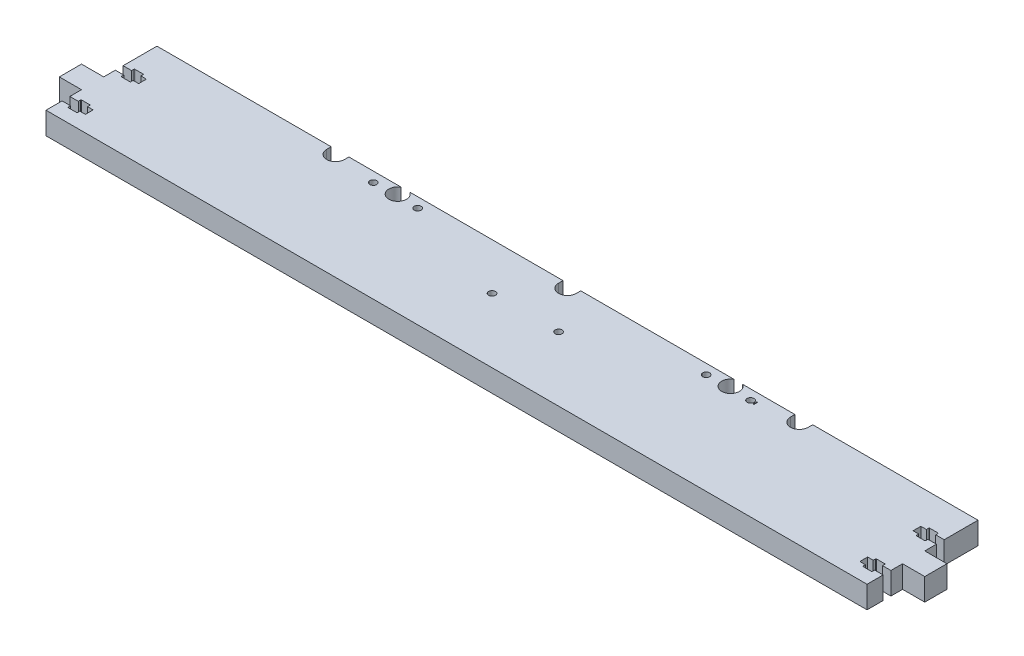
SolidWorks part; units mm, degrees
ref_plane "Front Plane" through (0, 0, 0) normal (0, 0, 1) x (1, 0, 0)
ref_plane "Top Plane" through (0, 0, 0) normal (0, 1, 0) x (1, 0, 0)
ref_plane "Right Plane" through (0, 0, 0) normal (1, 0, 0) x (0, 0, -1)
sketch "Sketch1" plane through (0, 0, 0) normal (0, 1, 0) x (1, 0, 0)
  line L0 (0, 25) -> (0, -25)
  line L1 (-185, 25) -> (0, 25)
  line L2 (-185, 25) -> (-185, -25) construction
  line L3 (-185, -25) -> (0, -25)
  line L4 (-185, -4) -> (-195, -4) construction
  line L5 (-185, 25) -> (0, 0) construction
  line L6 (-185, -25) -> (0, 0) construction
  line L7 (-185, -9) -> (-195, -9)
  line L8 (-195, -9) -> (-195, 1)
  line L9 (-195, 1) -> (-185, 1)
  line L10 (-185, 1) -> (-185, 25)
  line L11 (-185, -9) -> (-185, -25)
  line L47 (0, -25) -> (0, 25) construction
  line L89 (0, -25) -> (0, 25) construction
  point P0 (0, 0)
  dimension "D1" = 185
  dimension "D25" = 25
  dimension "D4" = 50
  dimension "D3" = 21
  dimension "D5" = 10
  dimension "D6" = 10
  dimension "D7" = 5
extrude "MainBody" add sketch "Sketch1" along normal blind 10
sketch "Sketch5" plane through (0, 10, 0) normal (0, 1, 0) x (1, 0, 0)
  line L0 (-185, 8) -> (-174.5, 8) construction
  line L1 (-185, 1) -> (-185, 25) construction
  line L2 (-185, 9.75) -> (-174.5, 9.75) construction
  line L3 (-174.5, 9.75) -> (-174.5, 6.25) construction
  line L4 (-174.5, 6.25) -> (-185, 6.25) construction
  line L5 (-185, 9.75) -> (-181.2, 9.75)
  line L6 (-181.2, 9.75) -> (-181.2, 10.75)
  line L7 (-180.95, 11) -> (-177.25, 11)
  line L8 (-177, 10.75) -> (-177, 9.75)
  line L9 (-177, 9.75) -> (-174.5, 9.75)
  line L10 (-174.5, 9.75) -> (-174.5, 6.25)
  line L11 (-185, 6.25) -> (-185, 9.75)
  line L12 (-195, -9) -> (-195, 1) construction
  line L13 (-185, 6.25) -> (-174.5, 6.25) construction
  line L14 (-177, 6.25) -> (-174.5, 6.25)
  line L15 (-177, 5.25) -> (-177, 6.25)
  line L16 (-180.95, 5) -> (-177.25, 5)
  line L17 (-181.2, 6.25) -> (-181.2, 5.25)
  line L18 (-185, 6.25) -> (-181.2, 6.25)
  line L19 (-185, 1) -> (-185, -9) construction
  line L20 (-195, -4) -> (-185, -4) construction
  line L21 (-195, -9) -> (-195, 1) construction
  line L22 (-185, -14.25) -> (-174.5, -14.25) construction
  line L23 (-174.5, -14.25) -> (-185, -14.25) construction
  line L24 (-174.5, -17.75) -> (-174.5, -14.25) construction
  line L25 (-185, -17.75) -> (-174.5, -17.75) construction
  line L26 (-185, -16) -> (-174.5, -16) construction
  line L27 (-185, -14.25) -> (-181.2, -14.25)
  line L28 (-181.2, -14.25) -> (-181.2, -13.25)
  line L29 (-180.95, -13) -> (-177.25, -13)
  line L30 (-177, -13.25) -> (-177, -14.25)
  line L31 (-177, -14.25) -> (-174.5, -14.25)
  line L32 (-185, -14.25) -> (-185, -17.75)
  line L33 (-174.5, -17.75) -> (-174.5, -14.25)
  line L34 (-177, -17.75) -> (-174.5, -17.75)
  line L35 (-177, -18.75) -> (-177, -17.75)
  line L36 (-180.95, -19) -> (-177.25, -19)
  line L37 (-181.2, -17.75) -> (-181.2, -18.75)
  line L38 (-185, -17.75) -> (-181.2, -17.75)
  line L39 (-185, 6.25) -> (-174.5, 6.25) construction
  arc A0 (-177.25, 11) -> (-177, 10.75) centre (-177.25, 10.75) cw
  arc A1 (-181.2, 10.75) -> (-180.95, 11) centre (-180.95, 10.75) cw
  arc A2 (-181.2, 5.25) -> (-180.95, 5) centre (-180.95, 5.25) ccw
  arc A3 (-177.25, 5) -> (-177, 5.25) centre (-177.25, 5.25) ccw
  arc A4 (-177.25, -13) -> (-177, -13.25) centre (-177.25, -13.25) cw
  arc A5 (-181.2, -13.25) -> (-180.95, -13) centre (-180.95, -13.25) cw
  arc A6 (-181.2, -18.75) -> (-180.95, -19) centre (-180.95, -18.75) ccw
  arc A7 (-177.25, -19) -> (-177, -18.75) centre (-177.25, -18.75) ccw
  point P6 (-195, -4)
  point P17 (-177, 11)
  point P20 (-181.2, 11)
  point P29 (-181.2, 5)
  point P30 (-177, 5)
  point P61 (-177, -13)
  point P62 (-181.2, -13)
  point P63 (-181.2, -19)
  point P64 (-177, -19)
  dimension "D8" = 0.25
  dimension "D1" = 10.5
  dimension "D2" = 1.75
  dimension "D4" = 4.2
  dimension "D5" = 8
  dimension "D6" = 3
  dimension "D7" = 12
extrude "ScrewCutouts" cut sketch "Sketch5" against normal through all
mirror "Mirror1" about plane through (0, 0, 0) normal (1, 0, 0) of "ScrewCutouts", "MainBody"
sketch "Sketch3" plane through (0, 10, 0) normal (0, 1, 0) x (1, 0, 0)
  line L0 (2, 25) -> (2, -25) construction
  line L1 (-185, 25) -> (185, 25) construction
  line L2 (-185, -25) -> (185, -25) construction
  line L3 (-63, 20.5) -> (-83, 20.5) construction
  line L4 (-73, 17.5) -> (-73, 25.5) construction
  line L5 (77, 17.5) -> (77, 25.5) construction
  line L6 (67, 20.5) -> (87, 20.5) construction
  circle A0 centre (-73, 21.5) radius 4
  circle A1 centre (-83, 20.5) radius 1.55
  circle A2 centre (-63, 20.5) radius 1.55
  circle A3 centre (67, 20.5) radius 1.55
  circle A4 centre (87, 20.5) radius 1.55
  circle A5 centre (77, 21.5) radius 4
  dimension "D2" = 8
  dimension "D4" = 3.1
  dimension "D1" = 3.5
  dimension "D5" = 75
  dimension "D6" = 2
  dimension "D3" = 10
  dimension "D7" = 1
extrude "RodCutouts" cut sketch "Sketch3" against normal through all
sketch "Sketch6" plane through (0, 10, 0) normal (0, 1, 0) x (1, 0, 0)
  line L0 (-73, 21.5) -> (77, 21.5) construction
  line L1 (2, 21.5) -> (2, -25) construction
  line L2 (-185, -25) -> (185, -25) construction
  line L3 (17, 4) -> (-13, 4) construction
  line L4 (-71.0635, 25) -> (75.0635, 25) construction
  circle A0 centre (-13, 4) radius 1.55
  circle A1 centre (17, 4) radius 1.55
  point P13 (2, 4)
  dimension "D3" = 21
  dimension "D1" = 3.1
  dimension "D2" = 15
extrude "Cut-Extrude1" cut sketch "Sketch6" against normal through all
sketch "Sketch7" plane through (0, 10, 0) normal (0, 1, 0) x (1, 0, 0)
  line L0 (-73, 21.5) -> (77, 21.5) construction
  line L1 (2, 21.5) -> (2, -25) construction
  line L3 (-102.5, 25) -> (-102.5, 23) construction
  line L4 (-185, 25) -> (-74.9365, 25) construction
  line L5 (-98.5, 25) -> (-98.5, 23)
  line L6 (-106.5, 25) -> (-106.5, 23)
  line L7 (106.5, 25) -> (106.5, 23) construction
  line L8 (102.5, 25) -> (102.5, 23)
  line L9 (110.5, 25) -> (110.5, 23)
  line L12 (-185, -25) -> (185, -25) construction
  arc A0 (-98.5, 25) -> (-106.5, 25) centre (-102.5, 25) ccw
  arc A1 (-106.5, 23) -> (-98.5, 23) centre (-102.5, 23) ccw
  arc A2 (102.5, 25) -> (110.5, 25) centre (106.5, 25) cw
  arc A3 (110.5, 23) -> (102.5, 23) centre (106.5, 23) cw
  point P12 (-102.5, 24)
  point P19 (106.5, 24)
  dimension "D1" = 4
  dimension "D2" = 2
  dimension "D3" = 104.5
extrude "BedAdjustmentScrewCutout" cut sketch "Sketch7" against normal through all
sketch "Sketch8" plane through (0, 10, 0) normal (0, 1, 0) x (1, 0, 0)
  line L0 (88.35, 20.5) -> (89.35, 20.5) construction
  line L1 (88.55, 20.5) -> (88.55, 25) construction
  line L2 (88.35, 20.5) -> (89.35, 21.5)
  line L3 (89.35, 21.5) -> (89.35, 19.5)
  line L4 (88.35, 20.5) -> (89.35, 19.5)
  line L5 (78.9365, 25) -> (102.5, 25) construction
  circle A1 centre (87, 20.5) radius 1.55 construction
  point P9 (89.35, 20.5)
  dimension "D1" = 1
  dimension "D2" = 1
  dimension "D3" = 0.2
extrude "DirectionKey" cut sketch "Sketch8" against normal through all
sketch "Sketch9" plane through (0, 10, 0) normal (0, 1, 0) x (1, 0, 0)
  line L0 (-13, 4) -> (17, 4) construction
  line L1 (2, 4) -> (2, 25) construction
  line L2 (-71.0635, 25) -> (75.0635, 25) construction
  line L3 (2, 27) -> (2, 23) construction
  line L4 (6, 27) -> (6, 23)
  line L5 (-2, 27) -> (-2, 23)
  arc A0 (6, 27) -> (-2, 27) centre (2, 27) ccw
  arc A1 (-2, 23) -> (6, 23) centre (2, 23) ccw
  point P10 (2, 25)
  dimension "D1" = 4
  dimension "D2" = 2
extrude "Cut-Extrude2" cut sketch "Sketch9" against normal through all
equation "\"Y-ROD-SPACING\"=75"
equation "\"Y-BED-OFFSET\"=2"
equation "\"T-SLOT-NUT-FILLET-RADIUS\"=0.25"
equation "\"T-SLOT-SCREW-SHAFT-RADIUS\"=1.75"
equation "\"T-SLOT-SCREW-SHAFT-CUTOUT-LENGTH\"=10.5"
equation "\"T-SLOT-NUT-DEPTH\"=4.2"
equation "\"T-SLOT-NUT-WIDTH\"=3"
equation "\"T-SLOT-NUT-END-DISTANCE\"=8"
equation "\"ACRYLIC-TAB-CUTOUT-SIZE\"=\"ACRYLIC-THICKNESS\"+\"ACRYLIC-TAB-TOLERANCE\"*2"
equation "\"ACRYLIC-M3-HOLE\"=3.1"
equation "\"D1@Sketch5\"=\"T-SLOT-SCREW-SHAFT-CUTOUT-LENGTH\""
equation "\"D2@Sketch5\"=\"T-SLOT-SCREW-SHAFT-RADIUS\""
equation "\"D4@Sketch5\"=\"T-SLOT-NUT-DEPTH\""
equation "\"D5@Sketch5\"=\"T-SLOT-NUT-END-DISTANCE\""
equation "\"D6@Sketch5\"=\"T-SLOT-NUT-WIDTH\""
equation "\"D8@Sketch5\"=\"T-SLOT-NUT-FILLET-RADIUS\""
equation "\"D4@Sketch3\"=\"ACRYLIC-M3-HOLE\""
equation "\"D5@Sketch3\"=\"Y-ROD-SPACING\""
equation "\"D6@Sketch3\"=\"Y-BED-OFFSET\""
equation "\"Y-BED-ROD-INSET\"=3.5"
equation "\"D1@Sketch3\"=\"Y-BED-ROD-INSET\""
equation "\"SMOOTHROD-CAP-SCREW-DISTANCE\"=20"
equation "\"D3@Sketch3\"=\"SMOOTHROD-CAP-SCREW-DISTANCE\"/2"
equation "\"ACRYLIC-TAB-WIDTH\"=\"ACRYLIC-THICKNESS\""
equation "\"FRAME-WIDTH-INNER\"=370"
equation "\"D6@Sketch1\"=\"ACRYLIC-TAB-WIDTH\""
equation "\"D5@Sketch1\"=\"ACRYLIC-TAB-WIDTH\""
equation "\"D1@Sketch1\"=\"FRAME-WIDTH-INNER\"/2"
equation "\"X-ROD-SPACING\"=45"
equation "\"Z-ROD-SPACING\"=17.5"
equation "\"ACRYLIC-THICKNESS\"=10"
equation "\"ACRYLIC-THICKNESS2\"=4.5"
equation "\"NEMA17-HOLE-SPACING\"=31"
equation "\"NEMA17-CENTRAL-CUTOUT\"=22.5"
equation "\"Z-BRACKET-REACH\"=55"
equation "\"TOP-BRACKET-SPACING\"=40"
equation "\"SMOOTHROD-X-LENGTH\"=350"
equation "\"SMOOTHROD-Y-LENGTH\"=350"
equation "\"SMOOTHROD-Z-LENGTH\"=350"
equation "\"SMOOTHROD-TIGHTENING-HEADROOM\"=.25"
equation "\"LEADSCREW-Z-LENGTH\"=300"
equation "\"SCREW-LENGTH-FRAME\"=\"ACRYLIC-THICKNESS\" + 10"
equation "\"SCREW-HEAD-RADIUS\"=6"
equation "\"PRINTED-X-SMOOTHROD-DIAMETER\"=8.2"
equation "\"PRINTED-X-SMOOTHROD-CUTOUT\"=10"
equation "\"PRINTED-X-BASE-HEIGHT\"=10"
equation "\"PRINTED-LM8UU-CUTOUT-SIZE\"=15.25"
equation "\"PRINTED-LM8UU-CUTOUT-LENGTH\"=24.5"
equation "\"PRINTED-X-IDLER-HEIGHT\"=16"
equation "\"PSU-MOUNTING-WIDTH\"=95"
equation "\"PSU-MOUNTING-HEIGHT\"=177"
equation "\"D1@MainBody\"=\"ACRYLIC-THICKNESS\""
equation "\"D7@Sketch1\"=\"ACRYLIC-TAB-WIDTH\"/2"
equation "\"D1@Sketch6\"=\"ACRYLIC-M3-HOLE\""
equation "\"Y-BELT-TO-ROD-DISTANCE\"=20"
equation "\"Y-BED-SCREW-SPACING\"=209"
equation "\"Z-ROD-INSET\"=16"
equation "\"SPOOL-HOLDER-ROD-SPACING\"=150"
equation "\"D3@Sketch7\"=\"Y-BED-SCREW-SPACING\"/2"
equation "\"Y-BED-SCREW-CUTOUT-SLOT-HEIGHT\"=2"
equation "\"D2@Sketch7\"=\"Y-BED-SCREW-CUTOUT-SLOT-HEIGHT\""
equation "\"ACRYLIC-TAB-TOLERANCE\"=.1"
equation "\"SCREW-LENGTH-MOTOR\"=\"ACRYLIC-THICKNESS\" + 5"
equation "\"SCREW-LENGTH-EXTRUDER\"=28"
equation "\"PRINTED-M3-HOLE\"=3.5"
equation "\"ACRYLIC-X-CARRIAGE-WIDTH\"=55"
equation "\"ACRYLIC-X-CARRIAGE-HEIGHT\"=75"
equation "\"ACRYLIC-X-CARRIAGE-LM8UU-CUTOUT-WIDTH\"=24.25"
equation "\"ACRYLIC-X-CARRIAGE-LM8UU-CUTOUT-HEIGHT\"=11.5"
equation "\"ACRYLIC-X-CARRIAGE-SCREW-SPACING-X\"=15"
equation "\"ACRYLIC-X-CARRIAGE-SCREW-SPACING-Y\"=33"
equation "\"ACRYLIC-X-CARRIAGE-CENTER-TAB-SPACING\"=14"
equation "\"ACRYLIC-X-CARRIAGE-EXTRUDER-OFFSET\"=26"
equation "\"ACRYLIC-X-CARRIAGE-EXTRUDER-ANGLE\"=90"
equation "\"ACRYLIC-X-CARRIAGE-EXTRUDER-SHELF-DEPTH\"=\"ACRYLIC-X-CARRIAGE-EXTRUDER-OFFSET\" + 28"
equation "\"ACRYLIC-X-CARRIAGE-EXTRUDER-BRACE-SPACING\"=23"
equation "\"ACRYLIC-X-CARRIAGE-EXTRUDER-BRACE-TAB-OFFSET\"=20"
equation "\"ACRYLIC-X-CARRIAGE-EXTRUDER-BRACE-HEIGHT\"=35"
equation "\"ACRYLIC-X-CARRIAGE-EXTRUDER-BRACE-SCREW-SPACING\"=22"
equation "\"ACRYLIC-X-CARRIAGE-DUAL-WIDTH-MULTIPLIER\"=1.65"
equation "\"ACRYLIC-X-CARRIAGE-DUAL-HOTEND-SPACING\"=42"
equation "\"ACRYLIC-X-CARRIAGE-DUAL-WIDTH\"=103"
equation "\"ACRYLIC-X-CARRIAGE-DUAL-HOTEND-SEPARATION\"=35"
equation "\"ACRYLIC-X-CARRIAGE-DUAL-MOUNT-PLATE-DEPTH\"=76"
equation "\"ACRYLIC-X-CARRIAGE-DUAL-MOUNT-BRACE-WIDTH\"=45"
equation "\"ACRYLIC-X-CARRIAGE-DUAL-MOUNT-SCREW-WIDTH\"=40"
equation "\"BLOWER-FAN-WIDTH\"=15"
equation "\"D2@Sketch9\"=\"Y-BED-SCREW-CUTOUT-SLOT-HEIGHT\""
